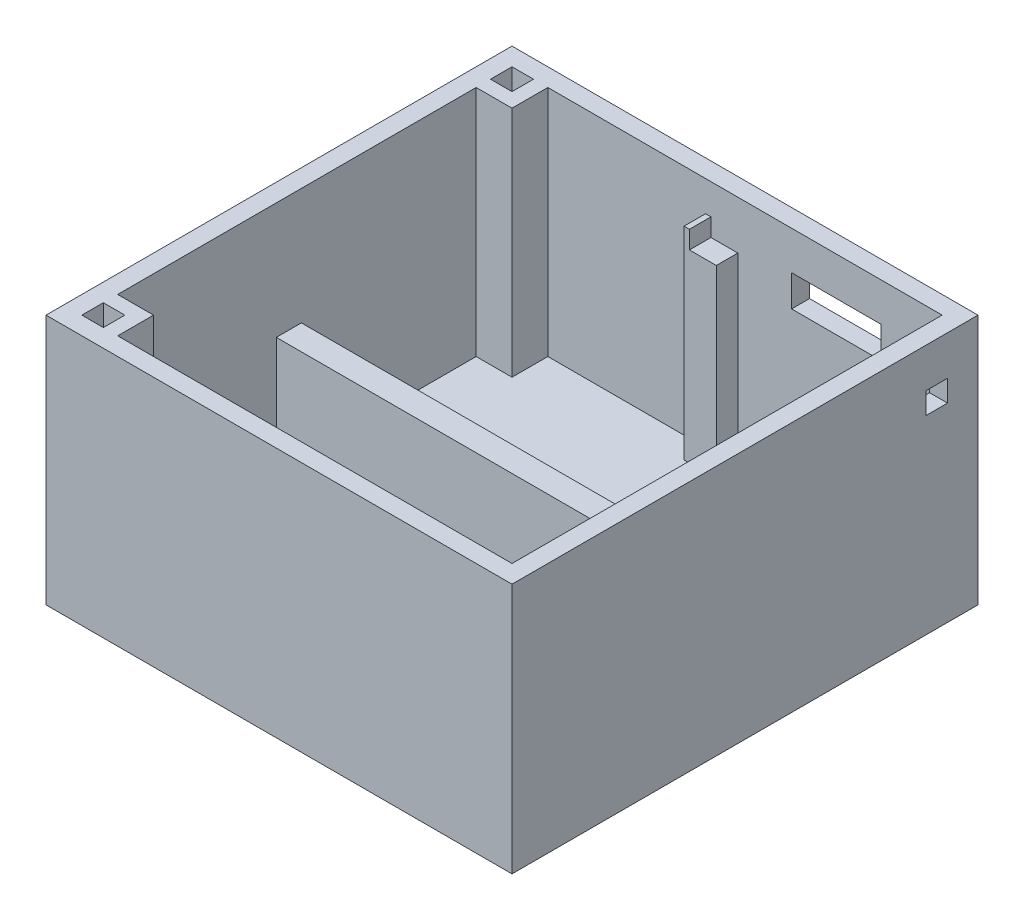
SolidWorks part; units mm, degrees
ref_plane "Ebene vorne" through (0, 0, 0) normal (0, 0, 1) x (1, 0, 0)
ref_plane "Ebene oben" through (0, 0, 0) normal (0, 1, 0) x (1, 0, 0)
ref_plane "Ebene rechts" through (0, 0, 0) normal (1, 0, 0) x (0, 0, -1)
sketch "Skizze1" plane through (0, 0, 0) normal (0, 1, 0) x (1, 0, 0)
  line L1 (-24, -24) -> (24, -24)
  line L2 (-24, -24) -> (-24, 24)
  line L3 (-24, 24) -> (24, 24)
  line L4 (24, -24) -> (24, 24)
  line L5 (-24, -24) -> (24, 24) construction
  line L6 (-24, 24) -> (24, -24) construction
  point P0 (0, 0)
  dimension "D1" = 48
  dimension "D2" = 48
extrude "Aufsatz-Linear austragen1" add sketch "Skizze1" along normal blind 2
sketch "Skizze2" plane through (0, 2, 0) normal (0, 1, 0) x (1, 0, 0)
  line L0 (-24, -24) -> (24, -24) construction
  line L1 (-24, -24) -> (24, -24)
  line L2 (24, -24) -> (24, 24) construction
  line L3 (24, 24) -> (-24, 24) construction
  line L4 (-24, 24) -> (-24, -24) construction
  line L5 (24, -24) -> (24, 24)
  line L6 (24, 24) -> (-24, 24)
  line L7 (-24, 24) -> (-24, -24)
extrude "Linear-Austragen-Dünn1" add sketch "Skizze2" along normal blind 26 and the other way up to surface (2 mm away) thin
sketch "Skizze4" plane through (0, 0, -26) normal (0, 0, -1) x (-1, 0, 0)
  line L0 (-26, 28) -> (26, 28) construction
  line L1 (-17.2, 20.2) -> (-7.2, 20.2)
  line L2 (-17.2, 20.2) -> (-17.2, 23.7)
  line L3 (-17.2, 23.7) -> (-7.2, 23.7)
  line L4 (-7.2, 20.2) -> (-7.2, 23.7)
  line L5 (-17.2, 20.2) -> (-7.2, 23.7) construction
  line L6 (-17.2, 23.7) -> (-7.2, 20.2) construction
  line L7 (-26, 0) -> (-26, 28) construction
  point P0 (-12.2, 21.95)
  dimension "D1" = 4.3
  dimension "D2" = 8.8
  dimension "D3" = 10
  dimension "D4" = 3.5
extrude "Schnitt-Linear austragen1" cut sketch "Skizze4" against normal up to next
sketch "Skizze5" plane through (26, 0, 0) normal (1, 0, 0) x (0, 0, -1)
  line L0 (-26, 28) -> (26, 28) construction
  line L1 (20.2, 21.2) -> (22.6, 21.2)
  line L2 (20.2, 21.2) -> (20.2, 23.6)
  line L3 (20.2, 23.6) -> (22.6, 23.6)
  line L4 (22.6, 21.2) -> (22.6, 23.6)
  line L5 (20.2, 21.2) -> (22.6, 23.6) construction
  line L6 (20.2, 23.6) -> (22.6, 21.2) construction
  line L7 (26, 0) -> (26, 28) construction
  line L8 (-26, 0) -> (26, 0) construction
  point P0 (21.4, 22.4)
  dimension "D1" = 4.4
  dimension "D2" = 5.8
  dimension "D3" = 21.2
  dimension "D4" = 2.4
extrude "Schnitt-Linear austragen2" cut sketch "Skizze5" against normal up to next
sketch "Skizze6" plane through (0, 2, 0) normal (0, 1, 0) x (1, 0, 0)
  line L1 (19, 16.6) -> (22, 16.6)
  line L2 (19, 16.6) -> (19, 21.4)
  line L3 (19, 21.4) -> (22, 21.4)
  line L4 (22, 16.6) -> (22, 21.4)
  line L5 (19, 16.6) -> (22, 21.4) construction
  line L6 (19, 21.4) -> (22, 16.6) construction
  line L8 (24, -24) -> (24, 24) construction
  point P0 (20.5, 19)
  dimension "D1" = 3
  dimension "D2" = 4.8
  dimension "D3" = 2
  dimension "D4" = 16.6
extrude "Aufsatz-Linear austragen2" add sketch "Skizze6" along normal blind 19.1
sketch "Skizze7" plane through (0, 2, 0) normal (0, 1, 0) x (1, 0, 0)
  line L1 (-2.4, 24) -> (1.2, 24)
  line L2 (-2.4, 24) -> (-2.4, 21.6)
  line L3 (-2.4, 21.6) -> (1.2, 21.6)
  line L4 (1.2, 24) -> (1.2, 21.6)
  line L5 (24, 24) -> (-24, 24) construction
  line L6 (19, 21.4) -> (19, 16.6) construction
  dimension "D1" = 17.8
  dimension "D2" = 3.6
  dimension "D3" = 2.4
extrude "Aufsatz-Linear austragen3" add sketch "Skizze7" along normal blind 20.6
sketch "Skizze8" plane through (0, 22.6, 0) normal (0, 1, 0) x (1, 0, 0)
  line L0 (24, 24) -> (-24, 24) construction
  line L1 (-2.4, 21.6) -> (-1.8, 21.6)
  line L2 (-2.4, 21.6) -> (-2.4, 24)
  line L3 (-2.4, 24) -> (-1.8, 24)
  line L4 (-1.8, 21.6) -> (-1.8, 24)
  dimension "D1" = 0.6
extrude "Aufsatz-Linear austragen4" add sketch "Skizze8" along normal blind 2
sketch "Skizze9" plane through (0, 2, 0) normal (0, 1, 0) x (1, 0, 0)
  line L0 (24, -24) -> (24, 24) construction
  line L1 (-13, -7.9) -> (24, -7.9)
  line L2 (-13, -7.9) -> (-13, -10.5)
  line L3 (-13, -10.5) -> (24, -10.5)
  line L4 (24, -7.9) -> (24, -10.5)
  line L5 (-24, -24) -> (24, -24) construction
  dimension "D1" = 13.5
  dimension "D2" = 2.6
  dimension "D3" = 13
extrude "Aufsatz-Linear austragen5" add sketch "Skizze9" along normal blind 20.6
sketch "Skizze10" plane through (0, 2, 0) normal (0, 1, 0) x (1, 0, 0)
  line L0 (-24, 21.6) -> (-21.6, 21.6)
  line L1 (-24, 24) -> (-24, -24) construction
  line L2 (-21.6, 21.6) -> (-21.6, 24)
  line L3 (24, 24) -> (-24, 24) construction
  line L4 (-21.6, 24) -> (-20, 24)
  line L5 (-2.4, 24) -> (-24, 24) construction
  line L6 (-20, 24) -> (-20, 20)
  line L7 (-20, 20) -> (-24, 20)
  line L8 (-24, 24) -> (-24, -24) construction
  line L9 (-24, -21.6) -> (-21.6, -21.6)
  line L10 (-21.6, -21.6) -> (-21.6, -24)
  line L11 (-24, -24) -> (24, -24) construction
  line L12 (-21.6, -24) -> (-20, -24)
  line L13 (-20, -24) -> (-20, -20)
  line L14 (-20, -20) -> (-24, -20)
  line L15 (-24, -20) -> (-24, -21.6)
  line L16 (-24, 20) -> (-24, 21.6)
  dimension "D1" = 2.4
  dimension "D2" = 4
extrude "Aufsatz-Linear austragen6" add sketch "Skizze10" along normal up to surface (26 mm away) up to face at (0, 28, 0)
sketch "Skizze11" plane through (0, 2, 0) normal (0, 1, 0) x (1, 0, 0)
  line L0 (24, -24) -> (24, -10.5) construction
  line L1 (-13, -10.5) -> (24, -10.5)
  line L2 (-13, -10.5) -> (-13, -13.3)
  line L3 (-13, -13.3) -> (24, -13.3)
  line L4 (24, -10.5) -> (24, -13.3)
  dimension "D1" = 2.8
extrude "Aufsatz-Linear austragen7" add sketch "Skizze11" along normal blind 24
